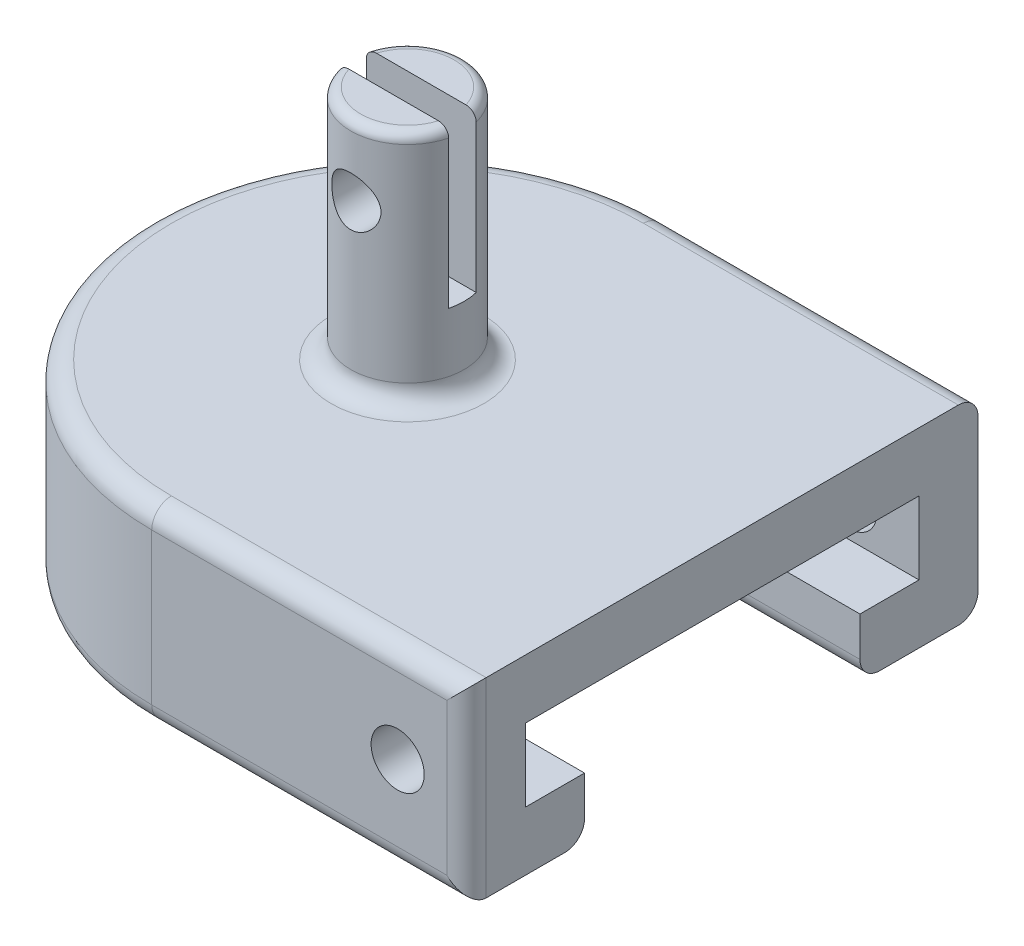
SolidWorks part; units mm, degrees
ref_plane "Front Plane" through (0, 0, 0) normal (0, 0, 1) x (1, 0, 0)
ref_plane "Top Plane" through (0, 0, 0) normal (0, 1, 0) x (1, 0, 0)
ref_plane "Right Plane" through (0, 0, 0) normal (1, 0, 0) x (0, 0, -1)
sketch "Sketch1" plane through (0, 0, 0) normal (0, 1, 0) x (1, 0, 0)
  line L0 (0, 13) -> (16, 13)
  line L1 (0, -13) -> (16, -13)
  line L2 (0, 7) -> (16, 7)
  line L3 (16, 13) -> (16, 7)
  line L4 (0, -7) -> (16, -7)
  line L5 (16, -7) -> (16, -13)
  arc A0 (0, 7) -> (0, -7) centre (0, 0) ccw
  arc A1 (0, 13) -> (0, -13) centre (0, 0) ccw
  dimension "D1" = 6
  dimension "D2" = 7
  dimension "D3" = 16
  dimension "D4" = 16
extrude "Boss-Extrude1" add sketch "Sketch1" along normal blind 3
sketch "Sketch2" plane through (0, 3, 0) normal (0, 1, 0) x (1, 0, 0)
  line L0 (0, 13) -> (16, 13)
  line L1 (16, 13) -> (16, 10)
  line L2 (16, 7) -> (16, 13) construction
  line L3 (16, -13) -> (0, -13)
  line L4 (16, -13) -> (16, -10)
  line L7 (16, -13) -> (16, -7) construction
  line L8 (0, 10) -> (16, 10)
  line L9 (0, -10) -> (16, -10)
  arc A0 (0, 10) -> (0, -10) centre (0, 0) ccw
  arc A1 (0, 13) -> (0, -13) centre (0, 0) ccw
  dimension "D2" = 3
extrude "Boss-Extrude2" add sketch "Sketch2" along normal blind 3.7
sketch "Sketch3" plane through (0, 6.7, 0) normal (0, 1, 0) x (1, 0, 0)
  line L0 (16, 13) -> (0, 13)
  line L1 (16, 13) -> (16, 7)
  line L3 (0, -13) -> (16, -13)
  line L4 (16, -13) -> (16, -7)
  line L5 (16, -7) -> (0, -7) construction
  line L6 (16, -10) -> (16, -7) construction
  line L8 (16, 7) -> (16, -7)
  arc A1 (0, 13) -> (0, -13) centre (0, 0) ccw
extrude "Boss-Extrude3" add sketch "Sketch3" along normal blind 3
sketch "Sketch4" plane through (0, 9.7, 0) normal (0, 1, 0) x (1, 0, 0)
  circle A0 centre (0, 0) radius 2.88
  dimension "D1" = 5.76
extrude "Boss-Extrude4" add sketch "Sketch4" along normal blind 12
hole_wizard "Ø2.5mm Dowel Hole1" positions "3DSketch4" profile "Sketch7" hole size "Ø2.5" standard "ANSI Metric" end condition through all
sketch3d "3DSketch4"
  point P0 (-0.0024, 18.1049, 2.88)
  point P12 (-0.0024, 18.1049, 2.88)
  point P15 (-0.0024, 18.1049, 2.88)
sketch "Sketch7" plane through (-0.0024, 18.1049, 2.88) normal (0, 1, 0) x (1, 0, 0.0008)
  line L0 (0, 0) -> (0, 15.8935)
  line L1 (0, 15.8935) -> (1.25, 15.8935)
  line L2 (1.25, 15.8935) -> (1.25, 0)
  line L5 (1.25, 0) -> (0, 0)
  line L11 (0, -6.35) -> (0, 107.95) construction
  dimension "Thru Hole Dia." = 2.5
  dimension "Thru Hole Depth" = 15.8935
sketch "Sketch8" plane through (0, 0, 13) normal (0, 0, 1) x (1, 0, 0)
  line L0 (16, 4.85) -> (0, 4.85) construction
  line L1 (16, 9.7) -> (16, 0) construction
  line L2 (0, 9.7) -> (0, 0) construction
  circle A0 centre (12.5, 4.85) radius 1.35
  dimension "D1" = 2.7
  dimension "D2" = 3.5
extrude "Cut-Extrude1" cut sketch "Sketch8" against normal through all
fillet "Fillet1" radius 1 10 edges at (8, 9.7, -13) (-13, 9.7, 0) (8, 0, -13) (-13, 0, 0) (8, 9.7, 13) (16, 4.85, 13) (8, 0, 13) (8, 0, -7) (-7, 0, 0) (8, 0, 7)
fillet "Fillet2" radius 1 1 edges at (0, 9.7, 2.88)
sketch "Sketch10" plane through (0, 21.7, 0) normal (0, 1, 0) x (1, 0, 0)
  line L0 (-2.7936, 0.7) -> (2.7936, 0.7)
  line L1 (-2.7936, -0.7) -> (2.7936, -0.7)
  line L2 (-2.88, 0) -> (2.88, 0) construction
  circle A0 centre (0, 0) radius 2.88 construction
  circle A1 centre (0, 0) radius 2.88 construction
  arc A2 (2.7936, -0.7) -> (2.7936, 0.7) centre (0, 0) ccw
  arc A3 (-2.7936, 0.7) -> (-2.7936, -0.7) centre (0, 0) ccw
  dimension "D2" = 0.7
  dimension "D3" = 0.7
extrude "Cut-Extrude2" cut sketch "Sketch10" against normal blind 8
fillet "Fillet3" radius 0.5 2 edges at (0, 21.7, -2.88) (0, 21.7, 2.88)
